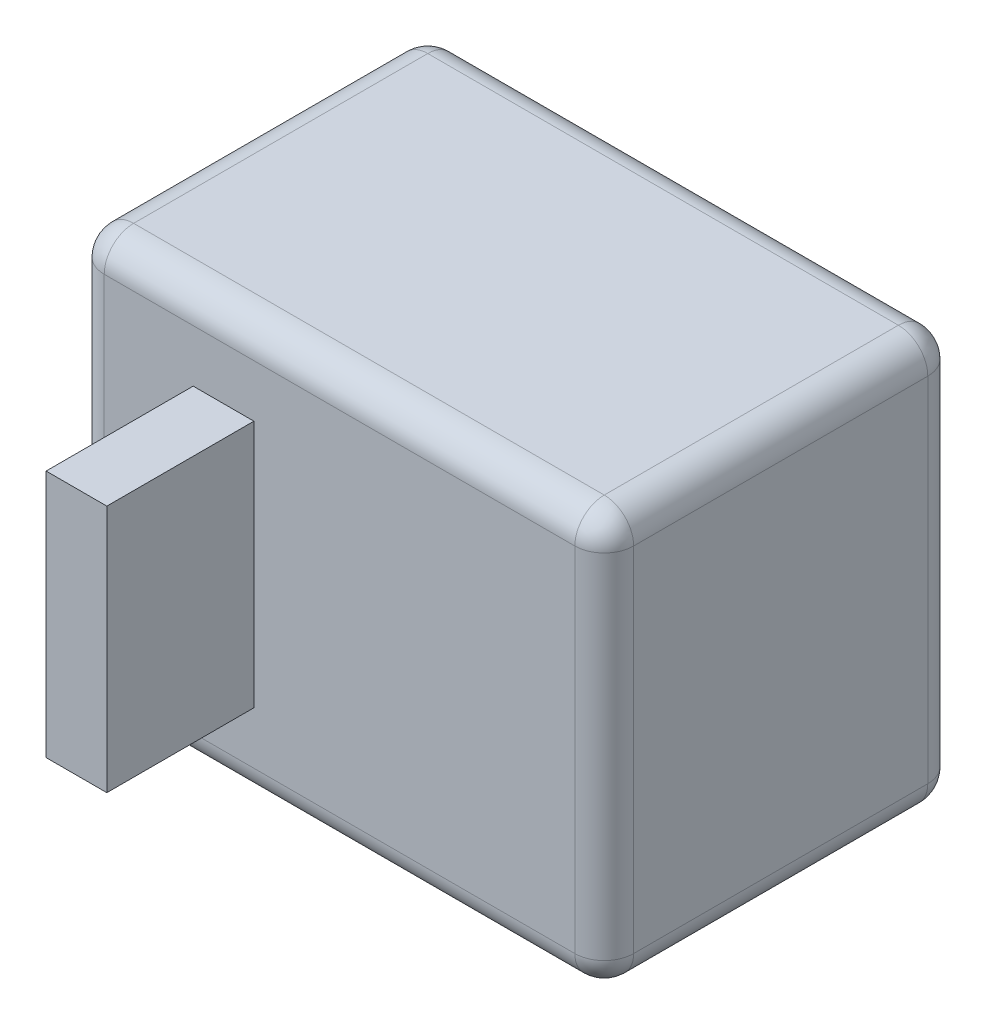
SolidWorks part; units mm, degrees
ref_plane "Спереди" through (0, 0, 0) normal (0, 0, 1) x (1, 0, 0)
ref_plane "Сверху" through (0, 0, 0) normal (0, 1, 0) x (1, 0, 0)
ref_plane "Справа" through (0, 0, 0) normal (1, 0, 0) x (0, 0, -1)
sketch "Эскиз1" plane through (0, 0, 0) normal (0, 0, 1) x (1, 0, 0)
  line L1 (-9, 7) -> (9, 7)
  line L2 (-9, 7) -> (-9, -7)
  line L3 (-9, -7) -> (9, -7)
  line L4 (9, 7) -> (9, -7)
  line L5 (-9, 7) -> (9, -7) construction
  line L6 (-9, -7) -> (9, 7) construction
  point P0 (0, 0)
  dimension "D1" = 18
  dimension "D2" = 14
extrude "Бобышка-Вытянуть1" add sketch "Эскиз1" along normal blind 12
sketch "Эскиз2" plane through (0, 0, 12) normal (0, 0, 1) x (1, 0, 0)
  line L1 (-4.9757, 4.2191) -> (-2.9108, 4.2191)
  line L2 (-4.9757, 4.2191) -> (-4.9757, -4.2191)
  line L3 (-4.9757, -4.2191) -> (-2.9108, -4.2191)
  line L4 (-2.9108, 4.2191) -> (-2.9108, -4.2191)
  line L5 (-4.9757, 4.2191) -> (-2.9108, -4.2191) construction
  line L6 (-4.9757, -4.2191) -> (-2.9108, 4.2191) construction
  point P0 (-3.9433, 0)
extrude "Бобышка-Вытянуть2" add sketch "Эскиз2" along normal blind 5
fillet "Скругление1" radius 1 12 edges at (0, 7, 12) (0, 7, 0) (-9, 7, 6) (-9, 0, 12) (-9, 0, 0) (9, 0, 12) (9, 7, 6) (9, 0, 0) (-9, -7, 6) (0, -7, 12) (9, -7, 6) (0, -7, 0)
